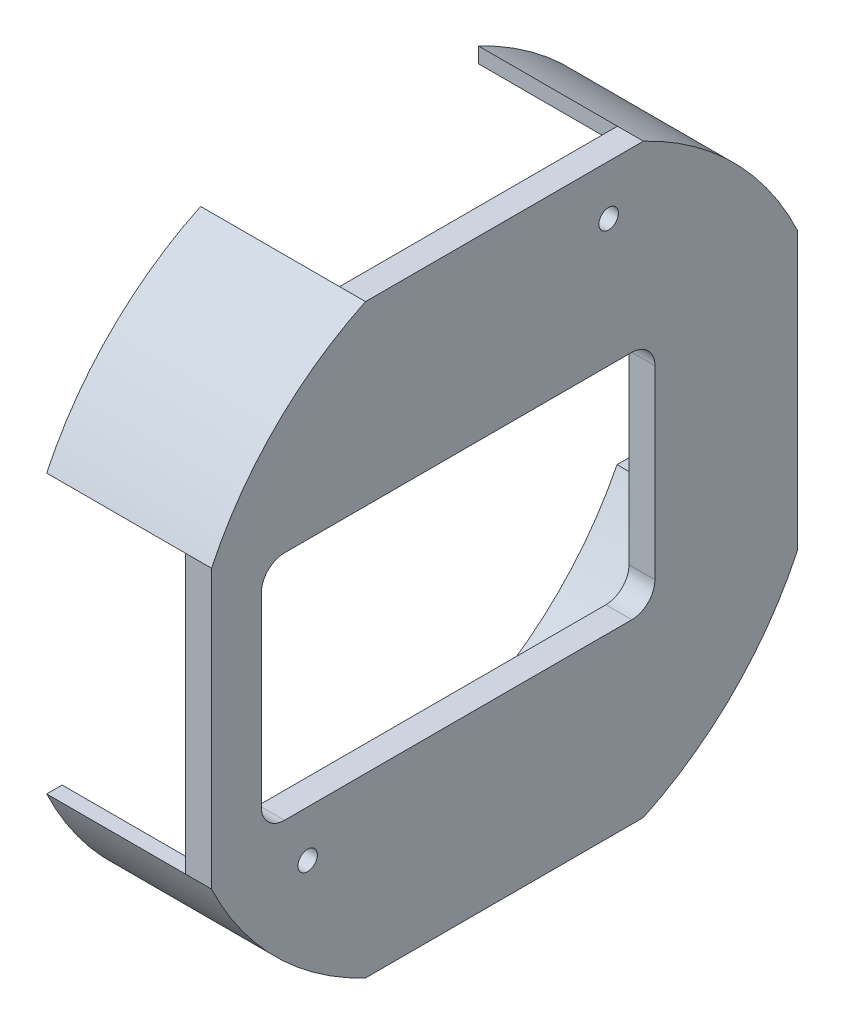
SolidWorks part; units mm, degrees
material "ﾎﾟﾘｴﾁﾚﾝｲﾐﾝ(PEI)"
ref_plane "正面" through (0, 0, 0) normal (0, 0, 1) x (1, 0, 0)
ref_plane "平面" through (0, 0, 0) normal (0, 1, 0) x (1, 0, 0)
ref_plane "右側面" through (0, 0, 0) normal (1, 0, 0) x (0, 0, -1)
sketch "ｽｹｯﾁ1" plane through (0, 0, 0) normal (1, 0, 0) x (0, 0, -1)
  line L0 (0, 0) -> (0, 52.5) construction
  line L1 (0, 52.5) -> (-32.5, 52.5) construction
  line L2 (0, 0) -> (10, 0) construction
  line L3 (-42.5, 25) -> (42.5, 25)
  line L4 (-42.5, 25) -> (-42.5, -25)
  line L5 (-42.5, -25) -> (42.5, -25)
  line L6 (42.5, 25) -> (42.5, -25)
  line L7 (-42.5, 25) -> (42.5, -25) construction
  line L8 (-42.5, -25) -> (42.5, 25) construction
  line L9 (-32.5, 52.5) -> (-32.5, -35) construction
  circle A2 centre (-32.5, 52.5) radius 2.1 construction
  circle A3 centre (32.5, 52.5) radius 2.1
  circle A4 centre (10, 0) radius 70
  circle A5 centre (-32.5, -35) radius 2.1
  dimension "D1" = 140
  dimension "D2" = 10
  dimension "D3" = 4.2
  dimension "D4" = 52.5
  dimension "D5" = 65
  dimension "D6" = 85
  dimension "D7" = 50
  dimension "D8" = 87.5
extrude "ﾎﾞｽ - 押し出し2" add sketch "ｽｹｯﾁ1" along normal blind 5.6
fillet "ﾌｨﾚｯﾄ1" radius 5 4 edges at (2.8, 25, 42.5) (2.8, -25, 42.5) (2.8, 25, -42.5) (2.8, -25, -42.5)
sketch "ｽｹｯﾁ2" plane through (0, 0, 0) normal (-1, 0, 0) x (0, 0, 1)
  line L0 (-73.2456, 30) -> (53.2456, 30)
  line L1 (20, 63.2456) -> (20, -63.2456)
  line L2 (-10, 70) -> (-10, 0) construction
  line L3 (-10, 0) -> (60, 0) construction
  line L4 (-73.2456, -30) -> (53.2456, -30)
  line L5 (-40, 63.2456) -> (-40, -63.2456)
  circle A0 centre (-10, 0) radius 67
  circle A1 centre (-10, 0) radius 70
  circle A2 centre (-10, 0) radius 70
  circle M9 centre (-10, 0) radius 70
  dimension "D3" = 60
  dimension "D4" = 60
  dimension "D1" = 0
  dimension "D2" = 3
extrude "ﾎﾞｽ - 押し出し3" add sketch "ｽｹｯﾁ2" along normal blind 30 contours A0 L5 L0 M9 | A0 L0 L1 M9 | A0 L4 L5 M9 | A0 L1 L4 M9
sketch "ｽｹｯﾁ3" plane through (0, 0, 0) normal (-1, 0, 0) x (0, 0, 1)
  line L0 (20, 63.2456) -> (-40, 63.2456)
  line L1 (-73.2456, 30) -> (-73.2456, -30)
  line L2 (-40, -63.2456) -> (20, -63.2456)
  line L3 (53.2456, -30) -> (53.2456, 30)
  line L8 (20, -63.2456) -> (20, -59.9083)
  line L9 (49.9083, -30) -> (53.2456, -30)
  line L10 (53.2456, 30) -> (49.9083, 30)
  line L11 (20, 59.9083) -> (20, 63.2456)
  line L12 (-40, 63.2456) -> (-40, 59.9083)
  line L13 (-69.9083, 30) -> (-73.2456, 30)
  line L14 (-73.2456, -30) -> (-69.9083, -30)
  line L15 (-40, -59.9083) -> (-40, -63.2456)
  line L16 (20, -63.2456) -> (20, -59.9083)
  line L17 (49.9083, -30) -> (53.2456, -30)
  line L18 (53.2456, 30) -> (49.9083, 30)
  line L19 (20, 59.9083) -> (20, 63.2456)
  line L20 (-40, 63.2456) -> (-40, 59.9083)
  line L21 (-69.9083, 30) -> (-73.2456, 30)
  line L22 (-73.2456, -30) -> (-69.9083, -30)
  line L23 (-40, -59.9083) -> (-40, -63.2456)
  arc A8 (20, -59.9083) -> (49.9083, -30) centre (-10, 0) ccw
  arc A9 (53.2456, -30) -> (53.2456, 30) centre (-10, 0) ccw
  arc A10 (49.9083, 30) -> (20, 59.9083) centre (-10, 0) ccw
  arc A11 (20, 63.2456) -> (-40, 63.2456) centre (-10, 0) ccw
  arc A12 (-40, 59.9083) -> (-69.9083, 30) centre (-10, 0) ccw
  arc A13 (-73.2456, 30) -> (-73.2456, -30) centre (-10, 0) ccw
  arc A14 (-69.9083, -30) -> (-40, -59.9083) centre (-10, 0) ccw
  arc A15 (-40, -63.2456) -> (20, -63.2456) centre (-10, 0) ccw
  arc A16 (20, -59.9083) -> (49.9083, -30) centre (-10, 0) ccw
  arc A17 (53.2456, -30) -> (53.2456, 30) centre (-10, 0) ccw
  arc A18 (49.9083, 30) -> (20, 59.9083) centre (-10, 0) ccw
  arc A19 (20, 63.2456) -> (-40, 63.2456) centre (-10, 0) ccw
  arc A20 (-40, 59.9083) -> (-69.9083, 30) centre (-10, 0) ccw
  arc A21 (-73.2456, 30) -> (-73.2456, -30) centre (-10, 0) ccw
  arc A22 (-69.9083, -30) -> (-40, -59.9083) centre (-10, 0) ccw
  arc A23 (-40, -63.2456) -> (20, -63.2456) centre (-10, 0) ccw
  arc M30 (53.2456, -30) -> (53.2456, 30) centre (-10, 0) ccw
  arc M34 (20, 63.2456) -> (-40, 63.2456) centre (-10, 0) ccw
  arc M38 (-73.2456, 30) -> (-73.2456, -30) centre (-10, 0) ccw
  arc M42 (-40, -63.2456) -> (20, -63.2456) centre (-10, 0) ccw
  dimension "D1" = 0
extrude "ｶｯﾄ - 押し出し1" cut sketch "ｽｹｯﾁ3" against normal through all contours L0 M34 | L1 M38 | L2 M42 | L3 M30
